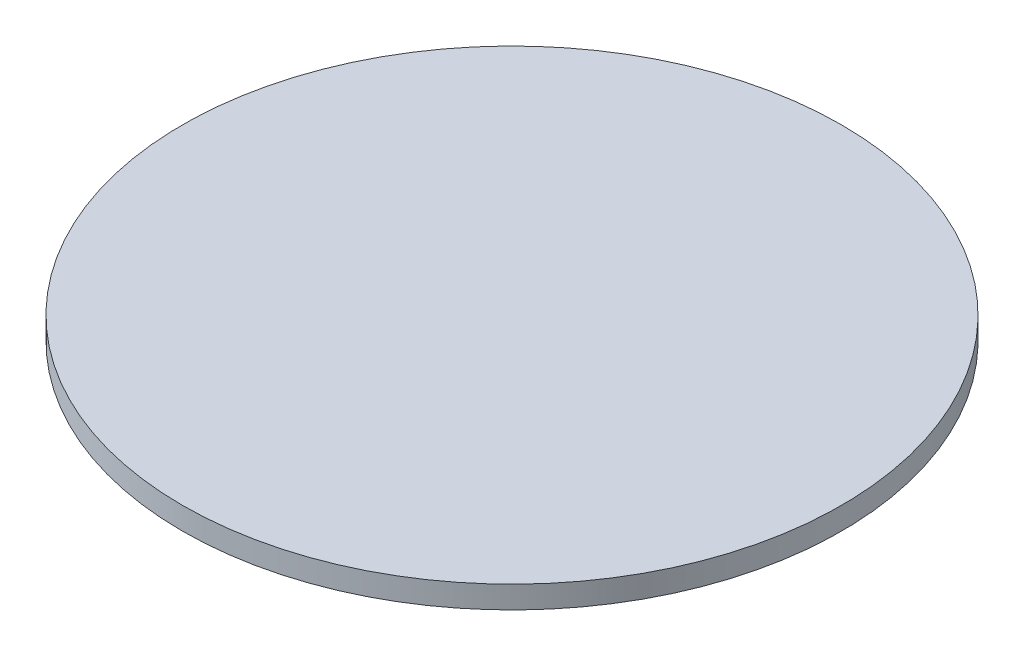
SolidWorks part; units mm, degrees
ref_plane "Front Plane" through (0, 0, 0) normal (0, 0, 1) x (1, 0, 0)
ref_plane "Top Plane" through (0, 0, 0) normal (0, 1, 0) x (1, 0, 0)
ref_plane "Right Plane" through (0, 0, 0) normal (1, 0, 0) x (0, 0, -1)
sketch "Sketch1" plane through (0, 0, 0) normal (0, 1, 0) x (1, 0, 0)
  circle A0 centre (0, 0) radius 118
  dimension "D1" = 236
extrude "Boss-Extrude1" add sketch "Sketch1" along normal blind 8 contours A0
